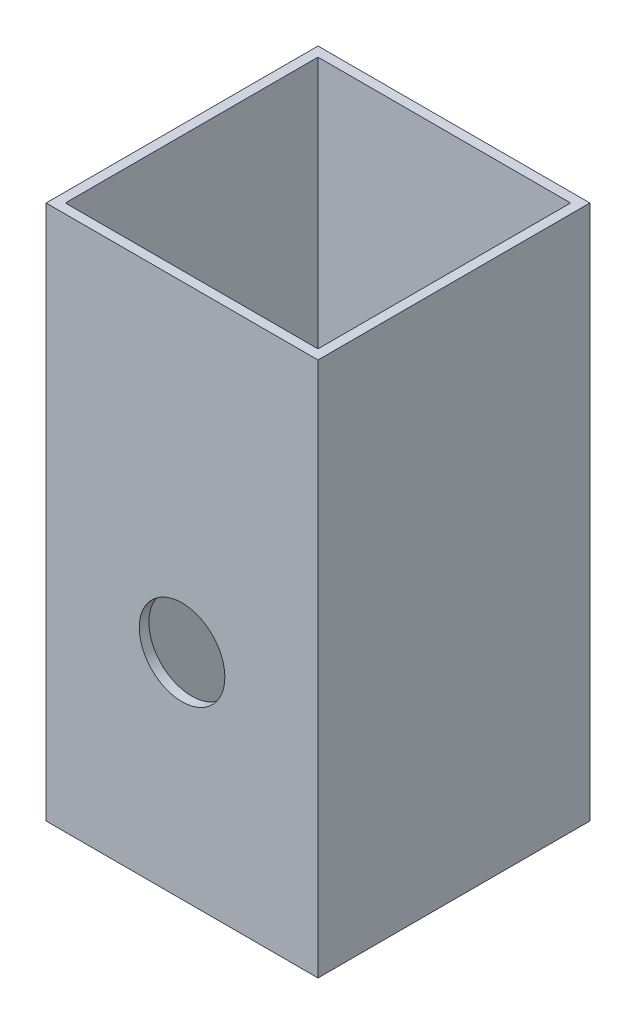
SolidWorks part; units mm, degrees
ref_plane "Front Plane" through (0, 0, 0) normal (0, 0, 1) x (1, 0, 0)
ref_plane "Top Plane" through (0, 0, 0) normal (0, 1, 0) x (1, 0, 0)
ref_plane "Right Plane" through (0, 0, 0) normal (1, 0, 0) x (0, 0, -1)
sketch "Sketch1" plane through (0, 0, 0) normal (0, 1, 0) x (1, 0, 0)
  line L0 (11.8, 11.8) -> (11.8, -11.8)
  line L1 (-12.7, 12.7) -> (12.7, 12.7)
  line L2 (-12.7, 12.7) -> (-12.7, -12.7)
  line L3 (-12.7, -12.7) -> (12.7, -12.7)
  line L4 (12.7, 12.7) -> (12.7, -12.7)
  line L5 (-12.7, 12.7) -> (12.7, -12.7) construction
  line L6 (-12.7, -12.7) -> (12.7, 12.7) construction
  line L7 (-11.8, -11.8) -> (11.8, -11.8)
  line L8 (-11.8, 11.8) -> (-11.8, -11.8)
  line L9 (-11.8, 11.8) -> (11.8, 11.8)
  point P0 (0, 0)
  dimension "D1" = 0.9
extrude "Boss-Extrude1" add sketch "Sketch1" along normal blind 50
sketch "Sketch2" plane through (0, 0, 12.7) normal (0, 0, 1) x (1, 0, 0)
  circle A0 centre (0, 20) radius 4
extrude "Cut-Extrude1" cut sketch "Sketch2" against normal blind 25.4
